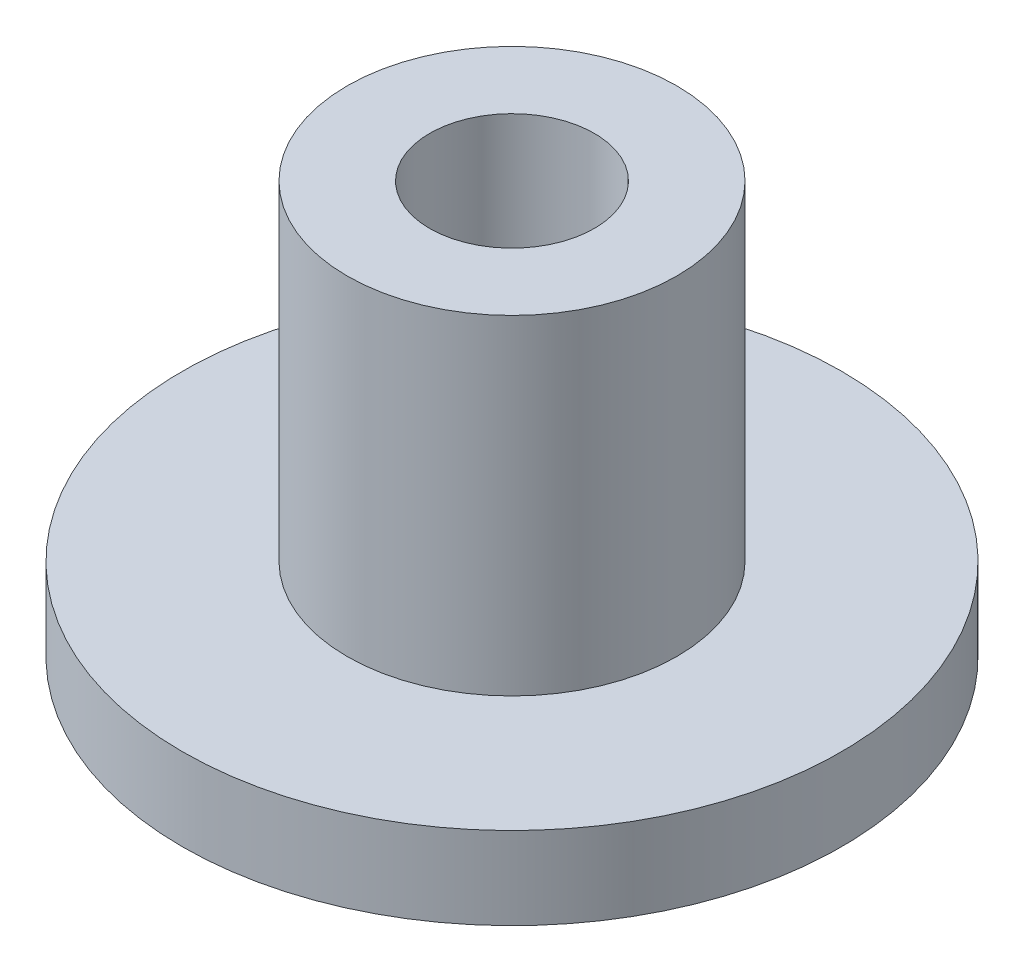
SolidWorks part; units mm, degrees
ref_plane "Front Plane" through (0, 0, 0) normal (0, 0, 1) x (1, 0, 0)
ref_plane "Top Plane" through (0, 0, 0) normal (0, 1, 0) x (1, 0, 0)
ref_plane "Right Plane" through (0, 0, 0) normal (1, 0, 0) x (0, 0, -1)
sketch "Sketch1" plane through (0, 0, 0) normal (0, 1, 0) x (1, 0, 0)
  circle A0 centre (0, 0) radius 4
extrude "Boss-Extrude1" add sketch "Sketch1" along normal blind 1
sketch "Sketch2" plane through (0, 1, 0) normal (0, 1, 0) x (1, 0, 0)
  circle A0 centre (0, 0) radius 2
extrude "Boss-Extrude2" add sketch "Sketch2" along normal blind 4
sketch "Sketch3" plane through (0, 5, 0) normal (0, 1, 0) x (1, 0, 0)
  circle A0 centre (0, 0) radius 1
extrude "Cut-Extrude1" cut sketch "Sketch3" against normal through all
